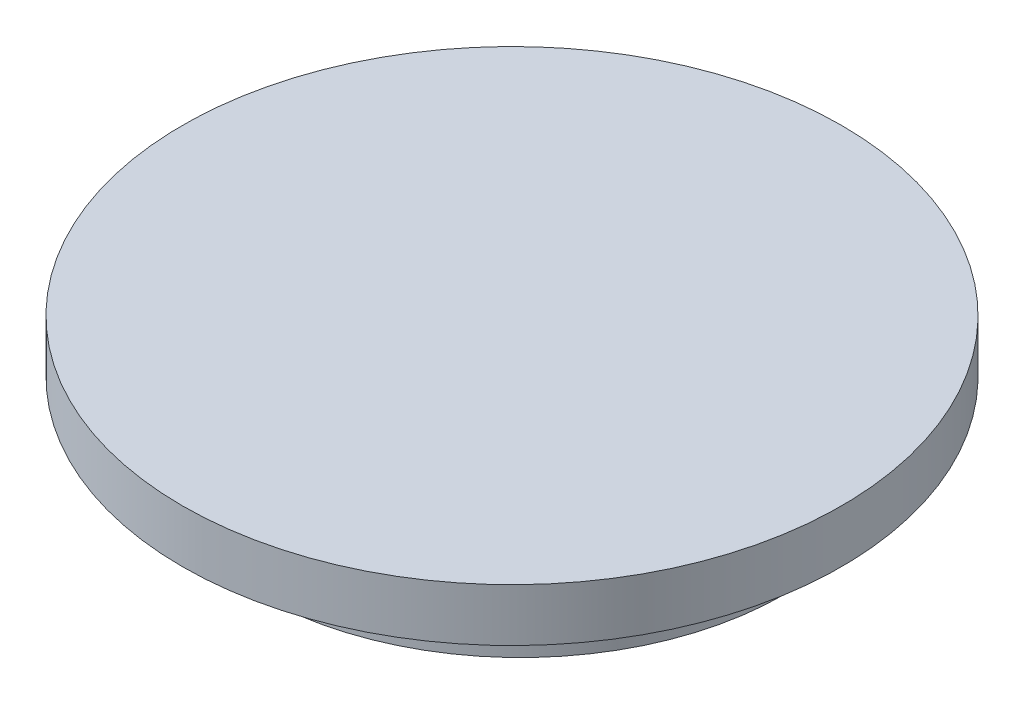
SolidWorks part; units mm, degrees
ref_plane "Front Plane" through (0, 0, 0) normal (0, 0, 1) x (1, 0, 0)
ref_plane "Top Plane" through (0, 0, 0) normal (0, 1, 0) x (1, 0, 0)
ref_plane "Right Plane" through (0, 0, 0) normal (1, 0, 0) x (0, 0, -1)
sketch "Sketch1" plane through (0, 0, 0) normal (0, 1, 0) x (1, 0, 0)
  circle A0 centre (0, 0) radius 20
  dimension "D1" = 40
extrude "Boss-Extrude1" add sketch "Sketch1" along normal blind 4
sketch "Sketch2" plane through (0, 4, 0) normal (0, 1, 0) x (1, 0, 0)
  circle A0 centre (-0.65, 0) radius 25
  dimension "D1" = 50
  dimension "D2" = 0.65
extrude "Boss-Extrude2" add sketch "Sketch2" along normal blind 4
